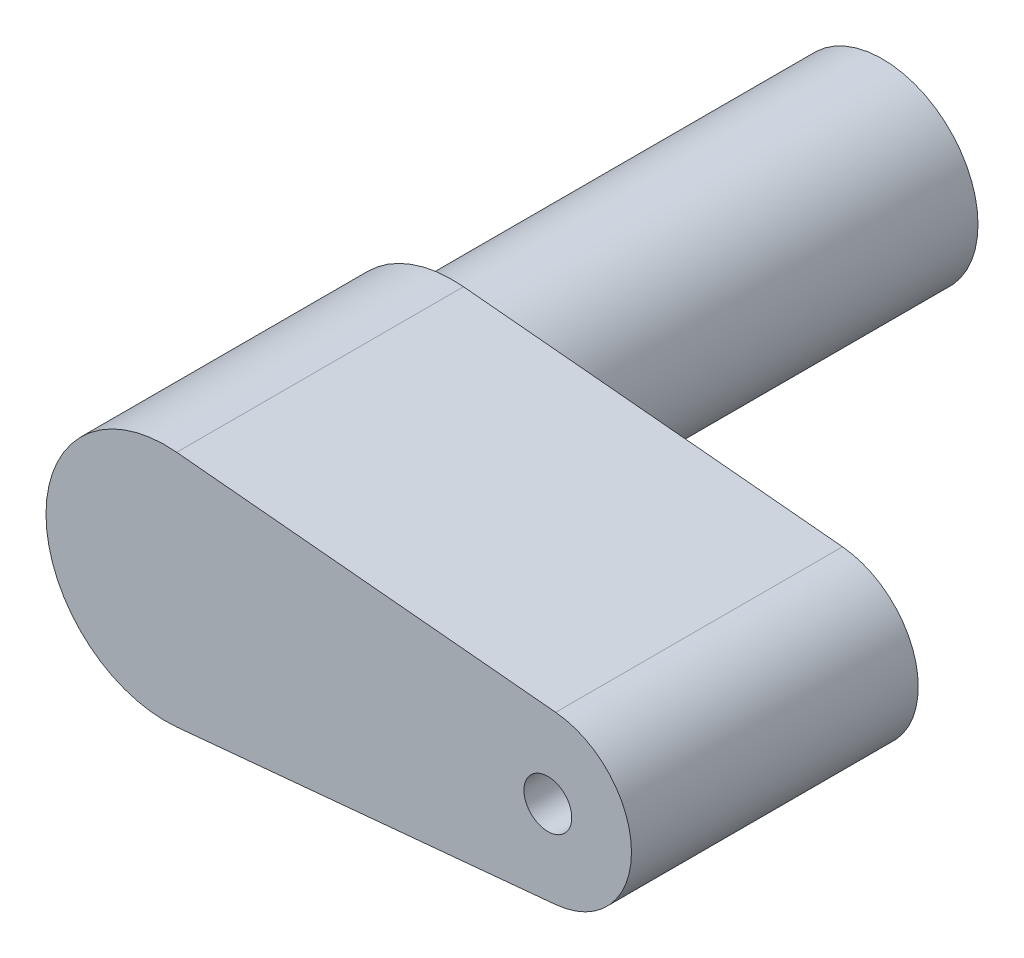
SolidWorks part; units mm, degrees
material "ABS"
ref_plane "Front Plane" through (0, 0, 0) normal (0, 0, 1) x (1, 0, 0)
ref_plane "Top Plane" through (0, 0, 0) normal (0, 1, 0) x (1, 0, 0)
ref_plane "Right Plane" through (0, 0, 0) normal (1, 0, 0) x (0, 0, -1)
sketch "Sketch1" plane through (0, 0, 0) normal (0, 0, 1) x (1, 0, 0)
  circle A0 centre (0, 491.0002) radius 1.25
  circle A1 centre (0, 491.0002) radius 4
extrude "Boss-Extrude1" add sketch "Sketch1" along normal blind 30
sketch "Sketch2" plane through (0, 0, 30) normal (0, 0, 1) x (1, 0, 0)
  line L0 (0, 491.0002) -> (16, 491.0002) construction
  line L5 (0.4687, 495.9782) -> (16.3281, 494.4848)
  line L6 (0.4687, 486.0222) -> (16.3281, 487.5156)
  arc A4 (0.4687, 495.9782) -> (0.4687, 486.0222) centre (0, 491.0002) ccw
  arc A5 (16.3281, 487.5156) -> (16.3281, 494.4848) centre (16, 491.0002) ccw
extrude "Boss-Extrude2" add sketch "Sketch2" against normal blind 12
sketch "Sketch3" plane through (0, 0, 30) normal (0, 0, 1) x (1, 0, 0)
  line L0 (-5, 491.0002) -> (19.5, 491.0002) construction
  arc A0 (0.4687, 495.9782) -> (0.4687, 486.0222) centre (0, 491.0002) ccw construction
  arc A1 (16.3281, 487.5156) -> (16.3281, 494.4848) centre (16, 491.0002) ccw construction
  circle A2 centre (16, 491.0002) radius 1
extrude "Cut-Extrude1" cut sketch "Sketch3" against normal up to surface (12 mm away) up to face at (4, 491.0002, 18)
